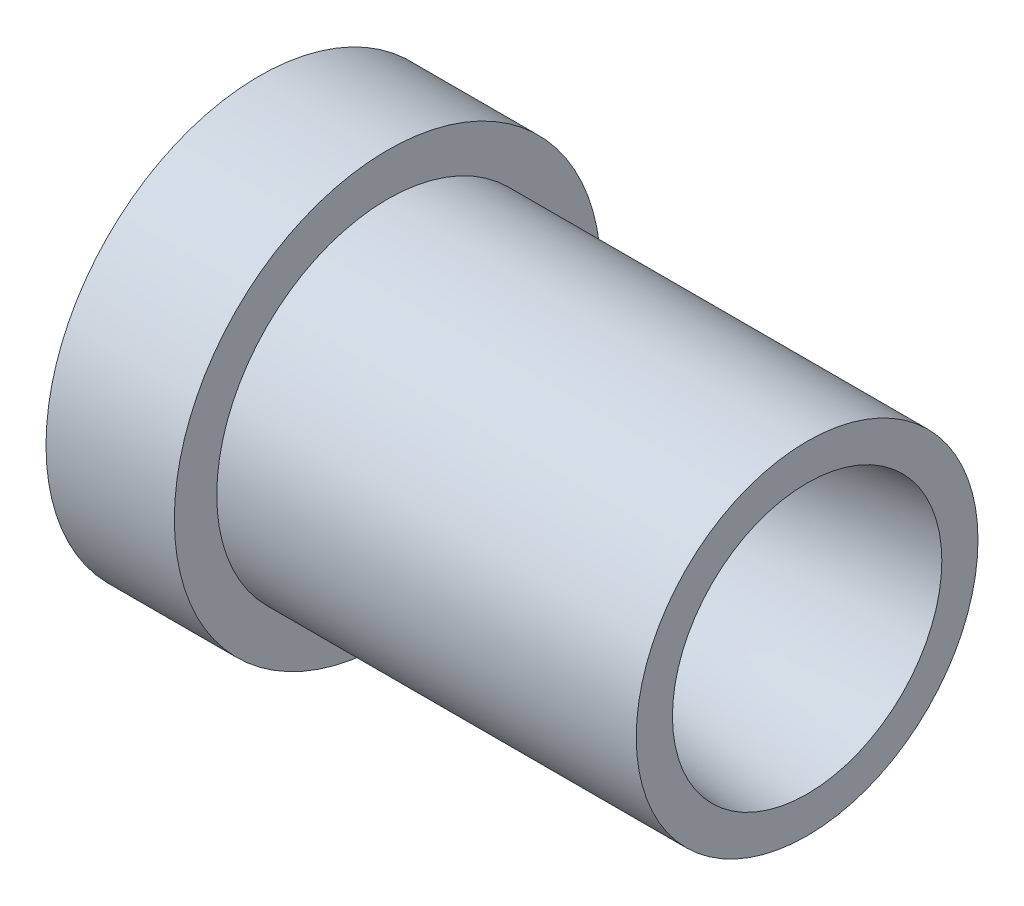
SolidWorks part; units mm, degrees
material "C (Graphite)"
ref_plane "Front Plane" through (0, 0, 0) normal (0, 0, 1) x (1, 0, 0)
ref_plane "Top Plane" through (0, 0, 0) normal (0, 1, 0) x (1, 0, 0)
ref_plane "Right Plane" through (0, 0, 0) normal (1, 0, 0) x (0, 0, -1)
curve "Curve1"
  spline degree 3 poles (-22.4867, 38.1, 0) (-22.3704, 38.099, 0) (-22.1376, 38.0969, 0) (-21.7888, 38.0803, 0) (-21.4407, 38.0539, 0) (-21.0935, 38.0166, 0) (-20.7477, 37.9687, 0) (-20.4035, 37.9104, 0) (-20.0612, 37.8415, 0) (-19.7211, 37.7622, 0) (-19.3837, 37.6726, 0) (-19.0491, 37.5727, 0) (-18.7178, 37.4626, 0) (-18.3899, 37.3425, 0) (-18.0659, 37.2124, 0) (-17.746, 37.0725, 0) (-17.4306, 36.9228, 0) (-17.1198, 36.7637, 0) (-16.8141, 36.5951, 0) (-16.5136, 36.4172, 0) (-16.2188, 36.2302, 0) (-15.9297, 36.0344, 0) (-15.6468, 35.8298, 0) (-15.3703, 35.6166, 0) (-15.1004, 35.3951, 0) (-14.8374, 35.1655, 0) (-14.5815, 34.9279, 0) (-14.333, 34.6826, 0) (-14.0921, 34.4299, 0) (-13.8591, 34.1699, 0) (-13.634, 33.9029, 0) (-13.4173, 33.6292, 0) (-13.209, 33.349, 0) (-13.0094, 33.0626, 0) (-12.8186, 32.7702, 0) (-12.6368, 32.4721, 0) (-12.4642, 32.1686, 0) (-12.3009, 31.8599, 0) (-12.1472, 31.5464, 0) (-12.0032, 31.2284, 0) (-11.8685, 30.9062, 0) (-11.7077, 30.4793, 0) (-11.5173, 29.9491, 0) (-11.2873, 29.3195, 0) (-11.0582, 28.6895, 0) (-10.8289, 28.0595, 0) (-10.5996, 27.4296, 0) (-10.3704, 26.7997, 0) (-10.1411, 26.1697, 0) (-9.9118, 25.5398, 0) (-9.6825, 24.9098, 0) (-9.4532, 24.2799, 0) (-9.224, 23.65, 0) (-8.9947, 23.02, 0) (-8.7654, 22.3901, 0) (-8.5361, 21.7601, 0) (-8.3068, 21.1302, 0) (-8.0776, 20.5003, 0) (-7.8482, 19.8703, 0) (-7.6192, 19.2403, 0) (-7.389, 18.6107, 0) (-7.2038, 18.0925, 0) (-7.0507, 17.6902, 0) (-6.9265, 17.4057, 0) (-6.7914, 17.1263, 0) (-6.6448, 16.8527, 0) (-6.4873, 16.5853, 0) (-6.319, 16.3245, 0) (-6.1402, 16.0707, 0) (-5.9513, 15.8245, 0) (-5.7525, 15.5861, 0) (-5.5441, 15.3561, 0) (-5.3266, 15.1347, 0) (-5.1002, 14.9224, 0) (-4.8653, 14.7194, 0) (-4.6224, 14.5262, 0) (-4.3719, 14.343, 0) (-4.114, 14.1702, 0) (-3.8494, 14.008, 0) (-3.5784, 13.8568, 0) (-3.3014, 13.7167, 0) (-3.019, 13.588, 0) (-2.7315, 13.4709, 0) (-2.4395, 13.3655, 0) (-2.1435, 13.2722, 0) (-1.844, 13.191, 0) (-1.5413, 13.1221, 0) (-1.2361, 13.0655, 0) (-0.9289, 13.0214, 0) (-0.6201, 12.9899, 0) (-0.3103, 12.9709, 0) (-0.0207, 12.9652, 0) (0.2483, 12.9688, 0) (0.4964, 12.9778, 0) (0.7442, 12.993, 0) (0.9915, 13.0142, 0) (1.2383, 13.0414, 0) (1.4844, 13.0747, 0) (1.7295, 13.1139, 0) (1.9736, 13.1593, 0) (2.2166, 13.2102, 0) (2.7411, 13.3365, 0) (3.5462, 13.5409, 0) (4.6351, 13.8109, 0) (5.7236, 14.0822, 0) (6.8122, 14.3527, 0) (7.9007, 14.6229, 0) (8.9893, 14.8926, 0) (10.0779, 15.1617, 0) (11.1664, 15.4302, 0) (12.255, 15.6981, 0) (13.3435, 15.9652, 0) (14.4321, 16.2314, 0) (15.5207, 16.4968, 0) (16.6092, 16.7612, 0) (17.6978, 17.0245, 0) (18.7864, 17.2868, 0) (19.8749, 17.5479, 0) (20.9635, 17.8077, 0) (22.0521, 18.0663, 0) (23.1406, 18.3234, 0) (24.2292, 18.5791, 0) (25.3178, 18.8333, 0) (26.4063, 19.0859, 0) (27.4949, 19.3368, 0) (28.5834, 19.5861, 0) (29.672, 19.8335, 0) (30.7606, 20.079, 0) (31.8491, 20.3227, 0) (32.9377, 20.5643, 0) (34.0263, 20.8039, 0) (35.1148, 21.0413, 0) (36.2034, 21.2765, 0) (37.292, 21.5094, 0) (38.3805, 21.74, 0) (39.4691, 21.9682, 0) (40.5577, 22.1939, 0) (41.6462, 22.417, 0) (42.7348, 22.6375, 0) (43.8234, 22.8554, 0) (44.9119, 23.0704, 0) (46.0005, 23.2827, 0) (47.0891, 23.492, 0) (48.1777, 23.6984, 0) (49.2662, 23.9017, 0) (50.3548, 24.1019, 0) (51.4434, 24.299, 0) (52.5319, 24.4928, 0) (53.6205, 24.6833, 0) (54.7091, 24.8704, 0) (55.7976, 25.0541, 0) (56.8862, 25.2342, 0) (57.9748, 25.4108, 0) (59.0634, 25.5836, 0) (60.1519, 25.7528, 0) (61.2405, 25.9182, 0) (62.3291, 26.0797, 0) (63.4176, 26.2373, 0) (64.5062, 26.3909, 0) (65.5948, 26.5404, 0) (66.6834, 26.6857, 0) (67.7719, 26.8269, 0) (68.8605, 26.9637, 0) (69.9491, 27.0963, 0) (71.0377, 27.2244, 0) (72.1262, 27.348, 0) (73.2148, 27.467, 0) (74.3034, 27.5815, 0) (75.392, 27.6912, 0) (76.4806, 27.7961, 0) (77.5691, 27.8966, 0) (78.295, 27.9594, 0) (78.6579, 27.9908, 0) knots 0 0 0 0 0.002987 0.005975 0.008962 0.011949 0.014937 0.017924 0.020911 0.023899 0.026886 0.029874 0.032861 0.035848 0.038836 0.041823 0.04481 0.047798 0.050785 0.053772 0.05676 0.059747 0.062734 0.065722 0.068709 0.071696 0.074684 0.077671 0.080658 0.083646 0.086633 0.089621 0.092608 0.095595 0.098583 0.10157 0.104557 0.107545 0.110532 0.113519 0.116507 0.119494 0.125231 0.130967 0.136704 0.14244 0.148177 0.153914 0.15965 0.165387 0.171123 0.17686 0.182597 0.188333 0.19407 0.199806 0.205543 0.21128 0.217016 0.222753 0.228489 0.234226 0.236881 0.239537 0.242192 0.244847 0.247503 0.250158 0.252813 0.255469 0.258124 0.260779 0.263435 0.26609 0.268745 0.271401 0.274056 0.276711 0.279367 0.282022 0.284677 0.287333 0.289988 0.292644 0.295299 0.297954 0.30061 0.303265 0.30592 0.308576 0.311231 0.313886 0.316011 0.318135 0.320259 0.322384 0.324508 0.326632 0.328757 0.330881 0.333006 0.33513 0.34473 0.354331 0.36393 0.373529 0.383127 0.392724 0.40232 0.411914 0.421507 0.431099 0.440689 0.450277 0.459863 0.469447 0.479029 0.488608 0.498185 0.50776 0.517332 0.5269 0.536466 0.546029 0.555589 0.565145 0.574698 0.584247 0.593793 0.603335 0.612873 0.622408 0.631938 0.641464 0.650986 0.660504 0.670017 0.679526 0.689031 0.698531 0.708026 0.717517 0.727003 0.736484 0.745961 0.755432 0.764899 0.774361 0.783818 0.793269 0.802716 0.812158 0.821596 0.831028 0.840455 0.849877 0.859294 0.868707 0.878114 0.887517 0.896915 0.906308 0.915697 0.925081 0.934461 0.943836 0.953207 0.962573 0.971936 0.981294 0.990649 1 1 1 1
sketch "Sketch1" plane through (0, 0, 0) normal (0, 0, 1) x (1, 0, 0)
  line L0 (-22.4867, 38.1) -> (-35.1867, 38.1)
  line L1 (-35.1867, 38.1) -> (-35.1867, 44.323)
  line L2 (-35.1867, 44.323) -> (-8.5167, 44.323)
  line L3 (-8.5167, 44.323) -> (-8.5167, 35.5092)
  line L4 (-8.5167, 35.5092) -> (78.6579, 35.5092)
  line L5 (78.6579, 35.5092) -> (78.6579, 27.9908)
  line L6 (-35.1867, 0) -> (78.6579, 0) construction
  spline S0 degree 3 poles (11.3679, 3037.5419) (-48.6308, 11.0625) (-34.9274, 38.7054) (-21.7888, 38.0803) (-21.4407, 38.0539) (-21.0935, 38.0166) (-20.7477, 37.9687) (-20.4035, 37.9104) (-20.0612, 37.8415) (-19.7211, 37.7622) (-19.3837, 37.6726) (-19.0491, 37.5727) (-18.7178, 37.4626) (-18.3899, 37.3425) (-18.0659, 37.2124) (-17.746, 37.0725) (-17.4306, 36.9228) (-17.1198, 36.7637) (-16.8141, 36.5951) (-16.5136, 36.4172) (-16.2188, 36.2302) (-15.9297, 36.0344) (-15.6468, 35.8298) (-15.3703, 35.6166) (-15.1004, 35.3951) (-14.8374, 35.1655) (-14.5815, 34.9279) (-14.333, 34.6826) (-14.0921, 34.4299) (-13.8591, 34.1699) (-13.634, 33.9029) (-13.4173, 33.6292) (-13.209, 33.349) (-13.0094, 33.0626) (-12.8186, 32.7702) (-12.6368, 32.4721) (-12.4642, 32.1686) (-12.3009, 31.8599) (-12.1472, 31.5464) (-12.0032, 31.2284) (-11.8685, 30.9062) (-11.7077, 30.4793) (-11.5173, 29.9491) (-11.2873, 29.3195) (-11.0582, 28.6895) (-10.8289, 28.0595) (-10.5996, 27.4296) (-10.3704, 26.7997) (-10.1411, 26.1697) (-9.9118, 25.5398) (-9.6825, 24.9098) (-9.4532, 24.2799) (-9.224, 23.65) (-8.9947, 23.02) (-8.7654, 22.3901) (-8.5361, 21.7601) (-8.3068, 21.1302) (-8.0776, 20.5003) (-7.8482, 19.8703) (-7.6192, 19.2403) (-7.389, 18.6107) (-7.2038, 18.0925) (-7.0507, 17.6902) (-6.9265, 17.4057) (-6.7914, 17.1263) (-6.6448, 16.8527) (-6.4873, 16.5853) (-6.319, 16.3245) (-6.1402, 16.0707) (-5.9513, 15.8245) (-5.7525, 15.5861) (-5.5441, 15.3561) (-5.3266, 15.1347) (-5.1002, 14.9224) (-4.8653, 14.7194) (-4.6224, 14.5262) (-4.3719, 14.343) (-4.114, 14.1702) (-3.8494, 14.008) (-3.5784, 13.8568) (-3.3014, 13.7167) (-3.019, 13.588) (-2.7315, 13.4709) (-2.4395, 13.3655) (-2.1435, 13.2722) (-1.844, 13.191) (-1.5413, 13.1221) (-1.2361, 13.0655) (-0.9289, 13.0214) (-0.6201, 12.9899) (-0.3103, 12.9709) (-0.0207, 12.9652) (0.2483, 12.9688) (0.4964, 12.9778) (0.7442, 12.993) (0.9915, 13.0142) (1.2383, 13.0414) (1.4844, 13.0747) (1.7295, 13.1139) (1.9736, 13.1593) (2.2166, 13.2102) (2.7411, 13.3365) (3.5462, 13.5409) (4.6351, 13.8109) (5.7236, 14.0822) (6.8122, 14.3527) (7.9007, 14.6229) (8.9893, 14.8926) (10.0779, 15.1617) (11.1664, 15.4302) (12.255, 15.6981) (13.3435, 15.9652) (14.4321, 16.2314) (15.5207, 16.4968) (16.6092, 16.7612) (17.6978, 17.0245) (18.7864, 17.2868) (19.8749, 17.5479) (20.9635, 17.8077) (22.0521, 18.0663) (23.1406, 18.3234) (24.2292, 18.5791) (25.3178, 18.8333) (26.4063, 19.0859) (27.4949, 19.3368) (28.5834, 19.5861) (29.672, 19.8335) (30.7606, 20.079) (31.8491, 20.3227) (32.9377, 20.5643) (34.0263, 20.8039) (35.1148, 21.0413) (36.2034, 21.2765) (37.292, 21.5094) (38.3805, 21.74) (39.4691, 21.9682) (40.5577, 22.1939) (41.6462, 22.417) (42.7348, 22.6375) (43.8234, 22.8554) (44.9119, 23.0704) (46.0005, 23.2827) (47.0891, 23.492) (48.1777, 23.6984) (49.2662, 23.9017) (50.3548, 24.1019) (51.4434, 24.299) (52.5319, 24.4928) (53.6205, 24.6833) (54.7091, 24.8704) (55.7976, 25.0541) (56.8862, 25.2342) (57.9748, 25.4108) (59.0634, 25.5836) (60.1519, 25.7528) (61.2405, 25.9182) (62.3291, 26.0797) (63.4176, 26.2373) (64.5062, 26.3909) (65.5948, 26.5404) (66.6834, 26.6857) (67.7719, 26.8269) (68.8605, 26.9637) (69.9491, 27.0963) (71.0377, 27.2244) (72.1262, 27.348) (73.2148, 27.467) (74.3034, 27.5815) (75.392, 27.6912) (76.4806, 27.7961) (129.2588, 32.6655) (183.5847, 15.985) (-31.0096, 3023.4548) knots -0.328637 -0.328637 -0.328637 -0.328637 0.002987 0.005975 0.008962 0.011949 0.014937 0.017924 0.020911 0.023899 0.026886 0.029874 0.032861 0.035848 0.038836 0.041823 0.04481 0.047798 0.050785 0.053772 0.05676 0.059747 0.062734 0.065722 0.068709 0.071696 0.074684 0.077671 0.080658 0.083646 0.086633 0.089621 0.092608 0.095595 0.098583 0.10157 0.104557 0.107545 0.110532 0.113519 0.116507 0.119494 0.125231 0.130967 0.136704 0.14244 0.148177 0.153914 0.15965 0.165387 0.171123 0.17686 0.182597 0.188333 0.19407 0.199806 0.205543 0.21128 0.217016 0.222753 0.228489 0.234226 0.236881 0.239537 0.242192 0.244847 0.247503 0.250158 0.252813 0.255469 0.258124 0.260779 0.263435 0.26609 0.268745 0.271401 0.274056 0.276711 0.279367 0.282022 0.284677 0.287333 0.289988 0.292644 0.295299 0.297954 0.30061 0.303265 0.30592 0.308576 0.311231 0.313886 0.316011 0.318135 0.320259 0.322384 0.324508 0.326632 0.328757 0.330881 0.333006 0.33513 0.34473 0.354331 0.36393 0.373529 0.383127 0.392724 0.40232 0.411914 0.421507 0.431099 0.440689 0.450277 0.459863 0.469447 0.479029 0.488608 0.498185 0.50776 0.517332 0.5269 0.536466 0.546029 0.555589 0.565145 0.574698 0.584247 0.593793 0.603335 0.612873 0.622408 0.631938 0.641464 0.650986 0.660504 0.670017 0.679526 0.689031 0.698531 0.708026 0.717517 0.727003 0.736484 0.745961 0.755432 0.764899 0.774361 0.783818 0.793269 0.802716 0.812158 0.821596 0.831028 0.840455 0.849877 0.859294 0.868707 0.878114 0.887517 0.896915 0.906308 0.915697 0.925081 0.934461 0.943836 0.953207 0.962573 0.971936 0.981294 0.990649 2.332615 2.332615 2.332615 2.332615 only from (-22.4867, 38.1) to (78.6579, 27.9908) construction
  spline S1 degree 3 poles (-22.4867, 38.1) (-22.3704, 38.099) (-22.1376, 38.0969) (-21.7888, 38.0803) (-21.4407, 38.0539) (-21.0935, 38.0166) (-20.7477, 37.9687) (-20.4035, 37.9104) (-20.0612, 37.8415) (-19.7211, 37.7622) (-19.3837, 37.6726) (-19.0491, 37.5727) (-18.7178, 37.4626) (-18.3899, 37.3425) (-18.0659, 37.2124) (-17.746, 37.0725) (-17.4306, 36.9228) (-17.1198, 36.7637) (-16.8141, 36.5951) (-16.5136, 36.4172) (-16.2188, 36.2302) (-15.9297, 36.0344) (-15.6468, 35.8298) (-15.3703, 35.6166) (-15.1004, 35.3951) (-14.8374, 35.1655) (-14.5815, 34.9279) (-14.333, 34.6826) (-14.0921, 34.4299) (-13.8591, 34.1699) (-13.634, 33.9029) (-13.4173, 33.6292) (-13.209, 33.349) (-13.0094, 33.0626) (-12.8186, 32.7702) (-12.6368, 32.4721) (-12.4642, 32.1686) (-12.3009, 31.8599) (-12.1472, 31.5464) (-12.0032, 31.2284) (-11.8685, 30.9062) (-11.7077, 30.4793) (-11.5173, 29.9491) (-11.2873, 29.3195) (-11.0582, 28.6895) (-10.8289, 28.0595) (-10.5996, 27.4296) (-10.3704, 26.7997) (-10.1411, 26.1697) (-9.9118, 25.5398) (-9.6825, 24.9098) (-9.4532, 24.2799) (-9.224, 23.65) (-8.9947, 23.02) (-8.7654, 22.3901) (-8.5361, 21.7601) (-8.3068, 21.1302) (-8.0776, 20.5003) (-7.8482, 19.8703) (-7.6192, 19.2403) (-7.389, 18.6107) (-7.2038, 18.0925) (-7.0507, 17.6902) (-6.9265, 17.4057) (-6.7914, 17.1263) (-6.6448, 16.8527) (-6.4873, 16.5853) (-6.319, 16.3245) (-6.1402, 16.0707) (-5.9513, 15.8245) (-5.7525, 15.5861) (-5.5441, 15.3561) (-5.3266, 15.1347) (-5.1002, 14.9224) (-4.8653, 14.7194) (-4.6224, 14.5262) (-4.3719, 14.343) (-4.114, 14.1702) (-3.8494, 14.008) (-3.5784, 13.8568) (-3.3014, 13.7167) (-3.019, 13.588) (-2.7315, 13.4709) (-2.4395, 13.3655) (-2.1435, 13.2722) (-1.844, 13.191) (-1.5413, 13.1221) (-1.2361, 13.0655) (-0.9289, 13.0214) (-0.6201, 12.9899) (-0.3103, 12.9709) (-0.0207, 12.9652) (0.2483, 12.9688) (0.4964, 12.9778) (0.7442, 12.993) (0.9915, 13.0142) (1.2383, 13.0414) (1.4844, 13.0747) (1.7295, 13.1139) (1.9736, 13.1593) (2.2166, 13.2102) (2.7411, 13.3365) (3.5462, 13.5409) (4.6351, 13.8109) (5.7236, 14.0822) (6.8122, 14.3527) (7.9007, 14.6229) (8.9893, 14.8926) (10.0779, 15.1617) (11.1664, 15.4302) (12.255, 15.6981) (13.3435, 15.9652) (14.4321, 16.2314) (15.5207, 16.4968) (16.6092, 16.7612) (17.6978, 17.0245) (18.7864, 17.2868) (19.8749, 17.5479) (20.9635, 17.8077) (22.0521, 18.0663) (23.1406, 18.3234) (24.2292, 18.5791) (25.3178, 18.8333) (26.4063, 19.0859) (27.4949, 19.3368) (28.5834, 19.5861) (29.672, 19.8335) (30.7606, 20.079) (31.8491, 20.3227) (32.9377, 20.5643) (34.0263, 20.8039) (35.1148, 21.0413) (36.2034, 21.2765) (37.292, 21.5094) (38.3805, 21.74) (39.4691, 21.9682) (40.5577, 22.1939) (41.6462, 22.417) (42.7348, 22.6375) (43.8234, 22.8554) (44.9119, 23.0704) (46.0005, 23.2827) (47.0891, 23.492) (48.1777, 23.6984) (49.2662, 23.9017) (50.3548, 24.1019) (51.4434, 24.299) (52.5319, 24.4928) (53.6205, 24.6833) (54.7091, 24.8704) (55.7976, 25.0541) (56.8862, 25.2342) (57.9748, 25.4108) (59.0634, 25.5836) (60.1519, 25.7528) (61.2405, 25.9182) (62.3291, 26.0797) (63.4176, 26.2373) (64.5062, 26.3909) (65.5948, 26.5404) (66.6834, 26.6857) (67.7719, 26.8269) (68.8605, 26.9637) (69.9491, 27.0963) (71.0377, 27.2244) (72.1262, 27.348) (73.2148, 27.467) (74.3034, 27.5815) (75.392, 27.6912) (76.4806, 27.7961) (77.5691, 27.8966) (78.295, 27.9594) (78.6579, 27.9908) knots 0 0 0 0 0.002987 0.005975 0.008962 0.011949 0.014937 0.017924 0.020911 0.023899 0.026886 0.029874 0.032861 0.035848 0.038836 0.041823 0.04481 0.047798 0.050785 0.053772 0.05676 0.059747 0.062734 0.065722 0.068709 0.071696 0.074684 0.077671 0.080658 0.083646 0.086633 0.089621 0.092608 0.095595 0.098583 0.10157 0.104557 0.107545 0.110532 0.113519 0.116507 0.119494 0.125231 0.130967 0.136704 0.14244 0.148177 0.153914 0.15965 0.165387 0.171123 0.17686 0.182597 0.188333 0.19407 0.199806 0.205543 0.21128 0.217016 0.222753 0.228489 0.234226 0.236881 0.239537 0.242192 0.244847 0.247503 0.250158 0.252813 0.255469 0.258124 0.260779 0.263435 0.26609 0.268745 0.271401 0.274056 0.276711 0.279367 0.282022 0.284677 0.287333 0.289988 0.292644 0.295299 0.297954 0.30061 0.303265 0.30592 0.308576 0.311231 0.313886 0.316011 0.318135 0.320259 0.322384 0.324508 0.326632 0.328757 0.330881 0.333006 0.33513 0.34473 0.354331 0.36393 0.373529 0.383127 0.392724 0.40232 0.411914 0.421507 0.431099 0.440689 0.450277 0.459863 0.469447 0.479029 0.488608 0.498185 0.50776 0.517332 0.5269 0.536466 0.546029 0.555589 0.565145 0.574698 0.584247 0.593793 0.603335 0.612873 0.622408 0.631938 0.641464 0.650986 0.660504 0.670017 0.679526 0.689031 0.698531 0.708026 0.717517 0.727003 0.736484 0.745961 0.755432 0.764899 0.774361 0.783818 0.793269 0.802716 0.812158 0.821596 0.831028 0.840455 0.849877 0.859294 0.868707 0.878114 0.887517 0.896915 0.906308 0.915697 0.925081 0.934461 0.943836 0.953207 0.962573 0.971936 0.981294 0.990649 1 1 1 1
revolve "Revolve1" add sketch "Sketch1" angle 360 about L6
